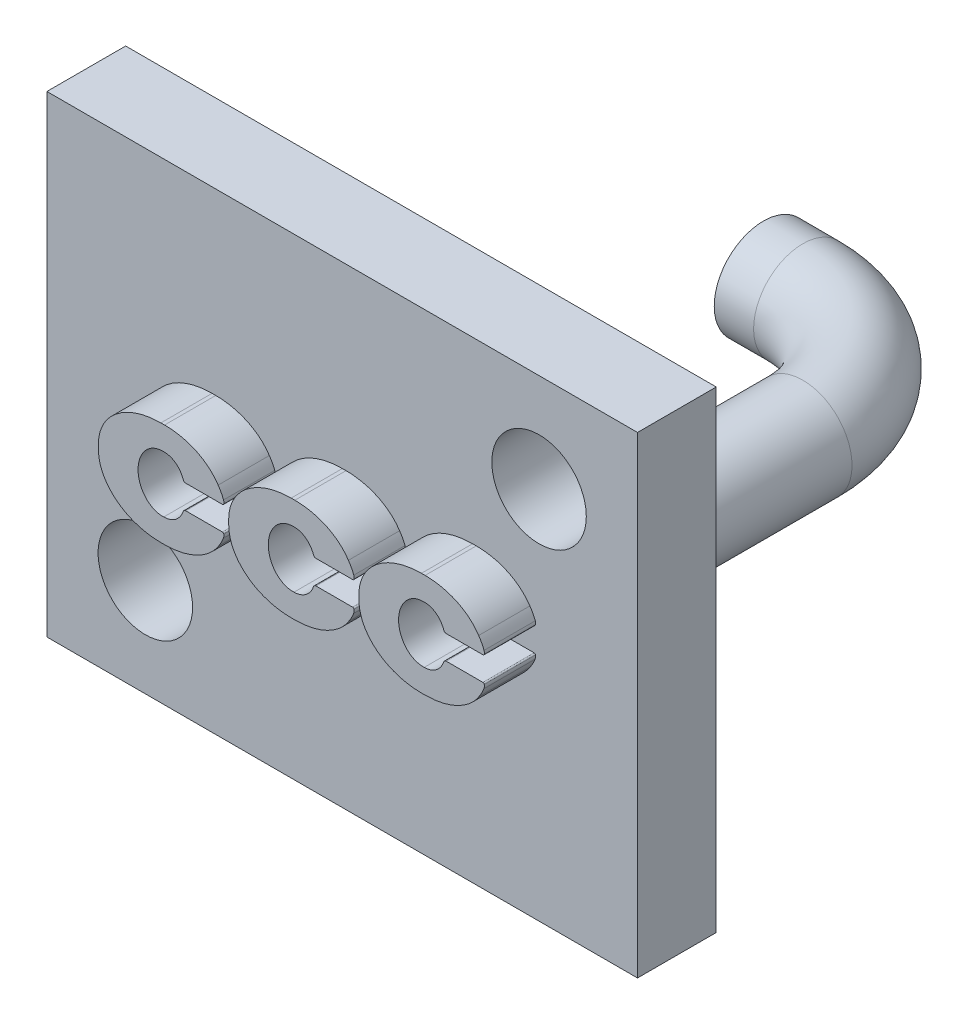
SolidWorks part; units mm, degrees
ref_plane "Front Plane" through (0, 0, 0) normal (0, 0, 1) x (1, 0, 0)
ref_plane "Top Plane" through (0, 0, 0) normal (0, 1, 0) x (1, 0, 0)
ref_plane "Right Plane" through (0, 0, 0) normal (1, 0, 0) x (0, 0, -1)
sketch "Sketch1" plane through (0, 0, 0) normal (0, 0, 1) x (1, 0, 0)
  line L1 (-7.5, 6) -> (7.5, 6)
  line L2 (-7.5, 6) -> (-7.5, -6)
  line L3 (-7.5, -6) -> (7.5, -6)
  line L4 (7.5, 6) -> (7.5, -6)
  line L5 (-7.5, 6) -> (7.5, -6) construction
  line L6 (-7.5, -6) -> (7.5, 6) construction
  point P0 (0, 0)
  dimension "D1" = 15
  dimension "D2" = 12
extrude "Boss-Extrude1" add sketch "Sketch1" along normal blind 2
sketch "Sketch2" plane through (0, 0, 2) normal (0, 0, 1) x (1, 0, 0)
  line L0 (0.6342, 0.4466) -> (1.5701, 0.4466)
  line L1 (0.0969, 1.4574) -> (0.0032, 1.4574)
  line L2 (-1.5824, 0.2062) -> (-1.5824, 0.0761)
  line L3 (0.0032, -1.1751) -> (0.0969, -1.1751)
  line L4 (1.5655, -0.1604) -> (0.6342, -0.1604)
  line L5 (-2.6741, 0.4466) -> (-1.7382, 0.4466)
  line L6 (-3.2115, 1.4574) -> (-3.3051, 1.4574)
  line L7 (-4.8907, 0.2062) -> (-4.8907, 0.0761)
  line L8 (-3.3051, -1.1751) -> (-3.2115, -1.1751)
  line L9 (-1.7428, -0.1604) -> (-2.6741, -0.1604)
  line L10 (3.9425, 0.4466) -> (4.8784, 0.4466)
  line L11 (3.4052, 1.4574) -> (3.3115, 1.4574)
  line L12 (1.7259, 0.2062) -> (1.7259, 0.0761)
  line L13 (3.3115, -1.1751) -> (3.4052, -1.1751)
  line L14 (4.8738, -0.1604) -> (3.9425, -0.1604)
  arc A0 (0.5725, 0.4902) -> (0.6342, 0.4466) centre (0.6342, 0.5121) ccw
  arc A1 (1.5701, 0.4466) -> (1.5993, 0.4715) centre (1.5656, 0.4815) ccw
  arc A2 (1.5993, 0.4715) -> (1.5951, 0.559) centre (1.4187, 0.5067) ccw
  arc A3 (1.5951, 0.559) -> (1.458, 0.8163) centre (0.5131, 0.1474) ccw
  arc A4 (1.458, -0.5339) -> (1.5904, -0.2876) centre (0.5225, 0.1277) ccw
  arc A5 (1.5904, -0.2876) -> (1.6002, -0.1896) centre (1.4189, -0.2209) ccw
  arc A6 (1.6002, -0.1896) -> (1.5655, -0.1604) centre (1.5655, -0.1956) ccw
  arc A7 (0.6342, -0.1604) -> (0.5725, -0.204) centre (0.6342, -0.2259) ccw
  arc A8 (-2.7358, 0.4902) -> (-2.6741, 0.4466) centre (-2.6741, 0.5121) ccw
  arc A9 (-1.7382, 0.4466) -> (-1.709, 0.4715) centre (-1.7427, 0.4815) ccw
  arc A10 (-1.709, 0.4715) -> (-1.7132, 0.559) centre (-1.8896, 0.5067) ccw
  arc A11 (-1.7132, 0.559) -> (-1.8504, 0.8163) centre (-2.7952, 0.1474) ccw
  arc A12 (-1.8504, -0.5339) -> (-1.7179, -0.2876) centre (-2.7858, 0.1277) ccw
  arc A13 (-1.7179, -0.2876) -> (-1.7081, -0.1896) centre (-1.8894, -0.2209) ccw
  arc A14 (-1.7081, -0.1896) -> (-1.7428, -0.1604) centre (-1.7428, -0.1956) ccw
  arc A15 (-2.6741, -0.1604) -> (-2.7358, -0.204) centre (-2.6741, -0.2259) ccw
  arc A16 (3.8808, 0.4902) -> (3.9425, 0.4466) centre (3.9425, 0.5121) ccw
  arc A17 (4.8784, 0.4466) -> (4.9076, 0.4715) centre (4.8739, 0.4815) ccw
  arc A18 (4.9076, 0.4715) -> (4.9034, 0.559) centre (4.727, 0.5067) ccw
  arc A19 (4.9034, 0.559) -> (4.7663, 0.8163) centre (3.8214, 0.1474) ccw
  arc A20 (4.7663, -0.5339) -> (4.8987, -0.2876) centre (3.8308, 0.1277) ccw
  arc A21 (4.8987, -0.2876) -> (4.9085, -0.1896) centre (4.7272, -0.2209) ccw
  arc A22 (4.9085, -0.1896) -> (4.8738, -0.1604) centre (4.8738, -0.1956) ccw
  arc A23 (3.9425, -0.1604) -> (3.8808, -0.204) centre (3.9425, -0.2259) ccw
  ellipse E0 centre (0.0443, 0.1413) end of major axis (0.0479, -0.5758) minor radius 0.6209 (0.0163, 0.8577) -> (0.0761, -0.5749) ccw
  ellipse E1 centre (-0.0118, 0.1413) end of major axis (-0.2944, -0.5403) minor radius 0.6039 (0.5725, 0.4902) -> (0.0163, 0.8577) ccw
  ellipse E2 centre (-0.0252, 0.1557) end of major axis (-1.668, -0.0894) minor radius 1.2925 (1.458, 0.8163) -> (0.0969, 1.4574) ccw
  ellipse E3 centre (0.0656, 0.157) end of major axis (-1.5793, 0.2864) minor radius 1.2979 (0.0032, 1.4574) -> (-1.5824, 0.2062) ccw
  ellipse E4 centre (0.0656, 0.1253) end of major axis (1.7105, 0.2547) minor radius 1.2979 (-1.5824, 0.0761) -> (0.0032, -1.1751) ccw
  ellipse E5 centre (-0.0252, 0.1266) end of major axis (1.6176, -0.1186) minor radius 1.2925 (0.0969, -1.1751) -> (1.458, -0.5339) ccw
  ellipse E6 centre (-0.0118, 0.1449) end of major axis (-0.2944, 0.8265) minor radius 0.6039 (0.0761, -0.5749) -> (0.5725, -0.204) ccw
  ellipse E7 centre (-3.3201, 0.1413) end of major axis (-3.6027, -0.5403) minor radius 0.6039 (-2.7358, 0.4902) -> (-3.292, 0.8577) ccw
  ellipse E8 centre (-3.3335, 0.1557) end of major axis (-1.6907, 0.4009) minor radius 1.2925 (-1.8504, 0.8163) -> (-3.2115, 1.4574) ccw
  ellipse E9 centre (-3.2427, 0.157) end of major axis (-1.5978, 0.0277) minor radius 1.2979 (-3.3051, 1.4574) -> (-4.8907, 0.2062) ccw
  ellipse E10 centre (-3.2427, 0.1253) end of major axis (-1.5978, 0.2547) minor radius 1.2979 (-4.8907, 0.0761) -> (-3.3051, -1.1751) ccw
  ellipse E11 centre (-3.3335, 0.1266) end of major axis (-1.6907, -0.1186) minor radius 1.2925 (-3.2115, -1.1751) -> (-1.8504, -0.5339) ccw
  ellipse E12 centre (-3.3201, 0.1449) end of major axis (-3.6027, 0.8265) minor radius 0.6039 (-3.2323, -0.5749) -> (-2.7358, -0.204) ccw
  ellipse E13 centre (-3.264, 0.1413) end of major axis (-3.2604, -0.5758) minor radius 0.6209 (-3.292, 0.8577) -> (-3.2323, -0.5749) ccw
  ellipse E14 centre (3.3526, 0.1413) end of major axis (3.3562, -0.5758) minor radius 0.6209 (3.3246, 0.8577) -> (3.3844, -0.5749) ccw
  ellipse E15 centre (3.2965, 0.1413) end of major axis (3.5792, 0.8229) minor radius 0.6039 (3.8808, 0.4902) -> (3.3246, 0.8577) ccw
  ellipse E16 centre (3.2831, 0.1557) end of major axis (4.9259, 0.4009) minor radius 1.2925 (4.7663, 0.8163) -> (3.4052, 1.4574) ccw
  ellipse E17 centre (3.3739, 0.157) end of major axis (1.729, 0.2864) minor radius 1.2979 (3.3115, 1.4574) -> (1.7259, 0.2062) ccw
  ellipse E18 centre (3.3739, 0.1253) end of major axis (5.0188, 0.2547) minor radius 1.2979 (1.7259, 0.0761) -> (3.3115, -1.1751) ccw
  ellipse E19 centre (3.2831, 0.1266) end of major axis (1.6403, 0.3717) minor radius 1.2925 (3.4052, -1.1751) -> (4.7663, -0.5339) ccw
  ellipse E20 centre (3.2965, 0.1449) end of major axis (3.0139, 0.8265) minor radius 0.6039 (3.3844, -0.5749) -> (3.8808, -0.204) ccw
extrude "Boss-Extrude2" add sketch "Sketch2" along normal blind 2
sketch "Sketch8" plane through (0, 0, 0) normal (0, 0, -1) x (-1, 0, 0)
  line L0 (7.4525, 0) -> (-7.4525, 0) construction
  line L1 (0, 0) -> (0, 0.9605) construction
  line L3 (0, 6) -> (0, -6) construction
  line L4 (-7.5, 6) -> (7.5, 6) construction
  line L5 (7.5, -6) -> (-7.5, -6) construction
  circle A0 centre (0.8, 0) radius 1.25
  circle A1 centre (-3.7443, 0) radius 1.25 construction
  dimension "D1" = 2.5
  dimension "D2" = 2.5
  dimension "D3" = 0.8
extrude "Boss-Extrude4" add sketch "Sketch8" along normal blind 4.5
sketch "Sketch7" plane through (0, 0, 0) normal (0, 0, -1) x (-1, 0, 0)
  line L0 (7.4525, 0) -> (-7.4525, 0) construction
  circle A0 centre (5.5, 0) radius 1.25
  dimension "D1" = 2.5
  dimension "D2" = 5.5
extrude "Boss-Extrude5" add sketch "Sketch7" along normal blind 4.5
sketch "Sketch9" plane through (0, 0, 0) normal (0, 1, 0) x (1, 0, 0)
  line L0 (3.6987, -2) -> (3.6987, 9) construction
  line L1 (7.5, 0) -> (-7.5, 0) construction
  line L2 (3.6987, 9) -> (-0.3013, 9) construction
  line L3 (3.6987, -0.2249) -> (3.6987, 6)
  line L4 (-0.3013, 9) -> (0.6987, 9)
  arc A0 (3.6987, 6) -> (0.6987, 9) centre (0.6987, 6) ccw
  dimension "D2" = 3
  dimension "D1" = 9
  dimension "D3" = 4
  dimension "D4" = 3.6987
sketch "Sketch10" plane through (0, 0, 0) normal (0, 0, -1) x (-1, 0, 0)
  line L0 (-0.6987, 0) -> (-3.6987, 0) construction
  line L1 (-3.6987, 0) -> (0.3013, 0) construction
  circle A0 centre (-3.6987, 0) radius 1.25
  dimension "D1" = 2.5
sweep "Sweep4" add profiles "Sketch10" path "Sketch9"
sketch "Sketch11" plane through (0, 0, 2) normal (0, 0, 1) x (1, 0, 0)
  line L0 (7.5, 6) -> (-7.5, 6) construction
  line L1 (7.5, -6) -> (7.5, 6) construction
  line L2 (-7.5, -6) -> (7.5, -6) construction
  line L3 (-7.5, 6) -> (-7.5, -6) construction
  circle A0 centre (-5, -3.5) radius 1.2
  circle A1 centre (5, 3.5) radius 1.2
  dimension "D5" = 2.4
  dimension "D1" = 2.5
  dimension "D2" = 2.5
  dimension "D3" = 2.5
  dimension "D4" = 2.5
extrude "Cut-Extrude1" cut sketch "Sketch11" against normal through all
sketch "Sketch13" plane through (0, 0, 4) normal (0, 0, 1) x (1, 0, 0)
  line L0 (0.6342, 0.4466) -> (1.5701, 0.4466) construction
  line L1 (0.0969, 1.4574) -> (0.0032, 1.4574) construction
  line L2 (-1.5824, 0.2062) -> (-1.5824, 0.0761) construction
  line L3 (0.0032, -1.1751) -> (0.0969, -1.1751) construction
  line L4 (1.5655, -0.1604) -> (0.6342, -0.1604) construction
  line L5 (-2.6741, 0.4466) -> (-1.7382, 0.4466)
  line L6 (-3.2115, 1.4574) -> (-3.3051, 1.4574)
  line L7 (-4.8907, 0.2062) -> (-4.8907, 0.0761)
  line L8 (-3.3051, -1.1751) -> (-3.2115, -1.1751)
  line L9 (-1.7428, -0.1604) -> (-2.6741, -0.1604)
  line L10 (-2.6741, 0.4466) -> (-1.7382, 0.4466)
  line L11 (-3.2115, 1.4574) -> (-3.3051, 1.4574)
  line L12 (-4.8907, 0.2062) -> (-4.8907, 0.0761)
  line L13 (-3.3051, -1.1751) -> (-3.2115, -1.1751)
  line L14 (-1.7428, -0.1604) -> (-2.6741, -0.1604)
  line L15 (3.9425, 0.4466) -> (4.8784, 0.4466) construction
  line L16 (3.4052, 1.4574) -> (3.3115, 1.4574) construction
  line L17 (1.7259, 0.2062) -> (1.7259, 0.0761) construction
  line L18 (3.3115, -1.1751) -> (3.4052, -1.1751) construction
  line L19 (4.8738, -0.1604) -> (3.9425, -0.1604) construction
  line L20 (0.6342, 0.4466) -> (1.5701, 0.4466)
  line L21 (0.0969, 1.4574) -> (0.0032, 1.4574)
  line L22 (-1.5824, 0.2062) -> (-1.5824, 0.0761)
  line L23 (0.0032, -1.1751) -> (0.0969, -1.1751)
  line L24 (1.5655, -0.1604) -> (0.6342, -0.1604)
  line L25 (3.9425, 0.4466) -> (4.8784, 0.4466)
  line L26 (3.4052, 1.4574) -> (3.3115, 1.4574)
  line L27 (1.7259, 0.2062) -> (1.7259, 0.0761)
  line L28 (3.3115, -1.1751) -> (3.4052, -1.1751)
  line L29 (4.8738, -0.1604) -> (3.9425, -0.1604)
  arc A0 (0.5725, 0.4902) -> (0.6342, 0.4466) centre (0.6342, 0.5121) ccw construction
  arc A1 (1.5701, 0.4466) -> (1.5993, 0.4715) centre (1.5656, 0.4815) ccw construction
  arc A2 (1.5993, 0.4715) -> (1.5951, 0.559) centre (1.4187, 0.5067) ccw construction
  arc A3 (1.5951, 0.559) -> (1.458, 0.8163) centre (0.5131, 0.1474) ccw construction
  arc A4 (1.458, -0.5339) -> (1.5904, -0.2876) centre (0.5225, 0.1277) ccw construction
  arc A5 (1.5904, -0.2876) -> (1.6002, -0.1896) centre (1.4189, -0.2209) ccw construction
  arc A6 (1.6002, -0.1896) -> (1.5655, -0.1604) centre (1.5655, -0.1956) ccw construction
  arc A7 (0.6342, -0.1604) -> (0.5725, -0.204) centre (0.6342, -0.2259) ccw construction
  arc A8 (-2.7358, 0.4902) -> (-2.6741, 0.4466) centre (-2.6741, 0.5121) ccw
  arc A9 (-1.7382, 0.4466) -> (-1.709, 0.4715) centre (-1.7427, 0.4815) ccw
  arc A10 (-1.709, 0.4715) -> (-1.7132, 0.559) centre (-1.8896, 0.5067) ccw
  arc A11 (-1.7132, 0.559) -> (-1.8504, 0.8163) centre (-2.7952, 0.1474) ccw
  arc A12 (-1.8504, -0.5339) -> (-1.7179, -0.2876) centre (-2.7858, 0.1277) ccw
  arc A13 (-1.7179, -0.2876) -> (-1.7081, -0.1896) centre (-1.8894, -0.2209) ccw
  arc A14 (-1.7081, -0.1896) -> (-1.7428, -0.1604) centre (-1.7428, -0.1956) ccw
  arc A15 (-2.6741, -0.1604) -> (-2.7358, -0.204) centre (-2.6741, -0.2259) ccw
  arc A16 (-2.7358, 0.4902) -> (-2.6741, 0.4466) centre (-2.6741, 0.5121) ccw
  arc A17 (-1.7382, 0.4466) -> (-1.709, 0.4715) centre (-1.7427, 0.4815) ccw
  arc A18 (-1.709, 0.4715) -> (-1.7132, 0.559) centre (-1.8896, 0.5067) ccw
  arc A19 (-1.7132, 0.559) -> (-1.8504, 0.8163) centre (-2.7952, 0.1474) ccw
  arc A20 (-1.8504, -0.5339) -> (-1.7179, -0.2876) centre (-2.7858, 0.1277) ccw
  arc A21 (-1.7179, -0.2876) -> (-1.7081, -0.1896) centre (-1.8894, -0.2209) ccw
  arc A22 (-1.7081, -0.1896) -> (-1.7428, -0.1604) centre (-1.7428, -0.1956) ccw
  arc A23 (-2.6741, -0.1604) -> (-2.7358, -0.204) centre (-2.6741, -0.2259) ccw
  arc A24 (3.8808, 0.4902) -> (3.9425, 0.4466) centre (3.9425, 0.5121) ccw construction
  arc A25 (4.8784, 0.4466) -> (4.9076, 0.4715) centre (4.8739, 0.4815) ccw construction
  arc A26 (4.9076, 0.4715) -> (4.9034, 0.559) centre (4.727, 0.5067) ccw construction
  arc A27 (4.9034, 0.559) -> (4.7663, 0.8163) centre (3.8214, 0.1474) ccw construction
  arc A28 (4.7663, -0.5339) -> (4.8987, -0.2876) centre (3.8308, 0.1277) ccw construction
  arc A29 (4.8987, -0.2876) -> (4.9085, -0.1896) centre (4.7272, -0.2209) ccw construction
  arc A30 (4.9085, -0.1896) -> (4.8738, -0.1604) centre (4.8738, -0.1956) ccw construction
  arc A31 (3.9425, -0.1604) -> (3.8808, -0.204) centre (3.9425, -0.2259) ccw construction
  arc A32 (0.5725, 0.4902) -> (0.6342, 0.4466) centre (0.6342, 0.5121) ccw
  arc A33 (1.5701, 0.4466) -> (1.5993, 0.4715) centre (1.5656, 0.4815) ccw
  arc A34 (1.5993, 0.4715) -> (1.5951, 0.559) centre (1.4187, 0.5067) ccw
  arc A35 (1.5951, 0.559) -> (1.458, 0.8163) centre (0.5131, 0.1474) ccw
  arc A36 (1.458, -0.5339) -> (1.5904, -0.2876) centre (0.5225, 0.1277) ccw
  arc A37 (1.5904, -0.2876) -> (1.6002, -0.1896) centre (1.4189, -0.2209) ccw
  arc A38 (1.6002, -0.1896) -> (1.5655, -0.1604) centre (1.5655, -0.1956) ccw
  arc A39 (0.6342, -0.1604) -> (0.5725, -0.204) centre (0.6342, -0.2259) ccw
  arc A40 (3.8808, 0.4902) -> (3.9425, 0.4466) centre (3.9425, 0.5121) ccw
  arc A41 (4.8784, 0.4466) -> (4.9076, 0.4715) centre (4.8739, 0.4815) ccw
  arc A42 (4.9076, 0.4715) -> (4.9034, 0.559) centre (4.727, 0.5067) ccw
  arc A43 (4.9034, 0.559) -> (4.7663, 0.8163) centre (3.8214, 0.1474) ccw
  arc A44 (4.7663, -0.5339) -> (4.8987, -0.2876) centre (3.8308, 0.1277) ccw
  arc A45 (4.8987, -0.2876) -> (4.9085, -0.1896) centre (4.7272, -0.2209) ccw
  arc A46 (4.9085, -0.1896) -> (4.8738, -0.1604) centre (4.8738, -0.1956) ccw
  arc A47 (3.9425, -0.1604) -> (3.8808, -0.204) centre (3.9425, -0.2259) ccw
  ellipse E0 centre (-0.0118, 0.1413) end of major axis (-0.2944, -0.5403) minor radius 0.6039 (0.5725, 0.4902) -> (0.0163, 0.8577) ccw construction
  ellipse E1 centre (-0.0252, 0.1557) end of major axis (1.6176, 0.4009) minor radius 1.2925 (1.458, 0.8163) -> (0.0969, 1.4574) ccw construction
  ellipse E2 centre (0.0656, 0.157) end of major axis (-1.5793, 0.2864) minor radius 1.2979 (0.0032, 1.4574) -> (-1.5824, 0.2062) ccw construction
  ellipse E3 centre (0.0656, 0.1253) end of major axis (1.7105, 0.2547) minor radius 1.2979 (-1.5824, 0.0761) -> (0.0032, -1.1751) ccw construction
  ellipse E4 centre (-0.0252, 0.1266) end of major axis (-1.668, 0.3717) minor radius 1.2925 (0.0969, -1.1751) -> (1.458, -0.5339) ccw construction
  ellipse E5 centre (-0.0118, 0.1449) end of major axis (0.2709, -0.5367) minor radius 0.6039 (0.0761, -0.5749) -> (0.5725, -0.204) ccw construction
  ellipse E6 centre (0.0443, 0.1413) end of major axis (0.0479, -0.5758) minor radius 0.6209 (0.0163, 0.8577) -> (0.0761, -0.5749) ccw construction
  ellipse E7 centre (-3.3201, 0.1413) end of major axis (-3.6027, -0.5403) minor radius 0.6039 (-2.7358, 0.4902) -> (-3.292, 0.8577) ccw
  ellipse E8 centre (-3.3335, 0.1557) end of major axis (-4.9763, -0.0894) minor radius 1.2925 (-1.8504, 0.8163) -> (-3.2115, 1.4574) ccw
  ellipse E9 centre (-3.2427, 0.157) end of major axis (-4.8876, 0.2864) minor radius 1.2979 (-3.3051, 1.4574) -> (-4.8907, 0.2062) ccw
  ellipse E10 centre (-3.2427, 0.1253) end of major axis (-1.5978, 0.2547) minor radius 1.2979 (-4.8907, 0.0761) -> (-3.3051, -1.1751) ccw
  ellipse E11 centre (-3.3335, 0.1266) end of major axis (-1.6907, -0.1186) minor radius 1.2925 (-3.2115, -1.1751) -> (-1.8504, -0.5339) ccw
  ellipse E12 centre (-3.3201, 0.1449) end of major axis (-3.0375, -0.5367) minor radius 0.6039 (-3.2323, -0.5749) -> (-2.7358, -0.204) ccw
  ellipse E13 centre (-3.264, 0.1413) end of major axis (-3.2604, -0.5758) minor radius 0.6209 (-3.292, 0.8577) -> (-3.2323, -0.5749) ccw
  ellipse E14 centre (-3.3201, 0.1413) end of major axis (-3.6027, -0.5403) minor radius 0.6039 (-2.7358, 0.4902) -> (-3.292, 0.8577) ccw
  ellipse E15 centre (-3.3335, 0.1557) end of major axis (-4.9763, -0.0894) minor radius 1.2925 (-1.8504, 0.8163) -> (-3.2115, 1.4574) ccw
  ellipse E16 centre (-3.2427, 0.157) end of major axis (-4.8876, 0.2864) minor radius 1.2979 (-3.3051, 1.4574) -> (-4.8907, 0.2062) ccw
  ellipse E17 centre (-3.2427, 0.1253) end of major axis (-1.5978, 0.2547) minor radius 1.2979 (-4.8907, 0.0761) -> (-3.3051, -1.1751) ccw
  ellipse E18 centre (-3.3335, 0.1266) end of major axis (-4.9763, 0.3717) minor radius 1.2925 (-3.2115, -1.1751) -> (-1.8504, -0.5339) ccw
  ellipse E19 centre (-3.3201, 0.1449) end of major axis (-3.0375, -0.5367) minor radius 0.6039 (-3.2323, -0.5749) -> (-2.7358, -0.204) ccw
  ellipse E20 centre (-3.264, 0.1413) end of major axis (-3.2604, -0.5758) minor radius 0.6209 (-3.292, 0.8577) -> (-3.2323, -0.5749) ccw
  ellipse E21 centre (3.2965, 0.1413) end of major axis (3.0139, -0.5403) minor radius 0.6039 (3.8808, 0.4902) -> (3.3246, 0.8577) ccw construction
  ellipse E22 centre (3.2831, 0.1557) end of major axis (1.6403, -0.0894) minor radius 1.2925 (4.7663, 0.8163) -> (3.4052, 1.4574) ccw construction
  ellipse E23 centre (3.3739, 0.157) end of major axis (1.729, 0.2864) minor radius 1.2979 (3.3115, 1.4574) -> (1.7259, 0.2062) ccw construction
  ellipse E24 centre (3.3739, 0.1253) end of major axis (1.729, -0.004) minor radius 1.2979 (1.7259, 0.0761) -> (3.3115, -1.1751) ccw construction
  ellipse E25 centre (3.2831, 0.1266) end of major axis (1.6403, 0.3717) minor radius 1.2925 (3.4052, -1.1751) -> (4.7663, -0.5339) ccw construction
  ellipse E26 centre (3.2965, 0.1449) end of major axis (3.5792, -0.5367) minor radius 0.6039 (3.3844, -0.5749) -> (3.8808, -0.204) ccw construction
  ellipse E27 centre (3.3526, 0.1413) end of major axis (3.3562, -0.5758) minor radius 0.6209 (3.3246, 0.8577) -> (3.3844, -0.5749) ccw construction
  ellipse E28 centre (-0.0118, 0.1413) end of major axis (-0.2944, -0.5403) minor radius 0.6039 (0.5725, 0.4902) -> (0.0163, 0.8577) ccw
  ellipse E29 centre (-0.0252, 0.1557) end of major axis (1.6176, 0.4009) minor radius 1.2925 (1.458, 0.8163) -> (0.0969, 1.4574) ccw
  ellipse E30 centre (0.0656, 0.157) end of major axis (-1.5793, 0.2864) minor radius 1.2979 (0.0032, 1.4574) -> (-1.5824, 0.2062) ccw
  ellipse E31 centre (0.0656, 0.1253) end of major axis (1.7105, 0.2547) minor radius 1.2979 (-1.5824, 0.0761) -> (0.0032, -1.1751) ccw
  ellipse E32 centre (-0.0252, 0.1266) end of major axis (-1.668, 0.3717) minor radius 1.2925 (0.0969, -1.1751) -> (1.458, -0.5339) ccw
  ellipse E33 centre (-0.0118, 0.1449) end of major axis (0.2709, -0.5367) minor radius 0.6039 (0.0761, -0.5749) -> (0.5725, -0.204) ccw
  ellipse E34 centre (0.0443, 0.1413) end of major axis (0.0479, -0.5758) minor radius 0.6209 (0.0163, 0.8577) -> (0.0761, -0.5749) ccw
  ellipse E35 centre (3.2965, 0.1413) end of major axis (3.0139, -0.5403) minor radius 0.6039 (3.8808, 0.4902) -> (3.3246, 0.8577) ccw
  ellipse E36 centre (3.2831, 0.1557) end of major axis (4.9259, 0.4009) minor radius 1.2925 (4.7663, 0.8163) -> (3.4052, 1.4574) ccw
  ellipse E37 centre (3.3739, 0.157) end of major axis (1.729, 0.2864) minor radius 1.2979 (3.3115, 1.4574) -> (1.7259, 0.2062) ccw
  ellipse E38 centre (3.3739, 0.1253) end of major axis (5.0188, 0.2547) minor radius 1.2979 (1.7259, 0.0761) -> (3.3115, -1.1751) ccw
  ellipse E39 centre (3.2831, 0.1266) end of major axis (1.6403, 0.3717) minor radius 1.2925 (3.4052, -1.1751) -> (4.7663, -0.5339) ccw
  ellipse E40 centre (3.2965, 0.1449) end of major axis (3.5792, -0.5367) minor radius 0.6039 (3.3844, -0.5749) -> (3.8808, -0.204) ccw
  ellipse E41 centre (3.3526, 0.1413) end of major axis (3.3562, -0.5758) minor radius 0.6209 (3.3246, 0.8577) -> (3.3844, -0.5749) ccw
  dimension "D1" = 0
extrude "Cut-Extrude2" cut sketch "Sketch13" against normal blind 0.7
